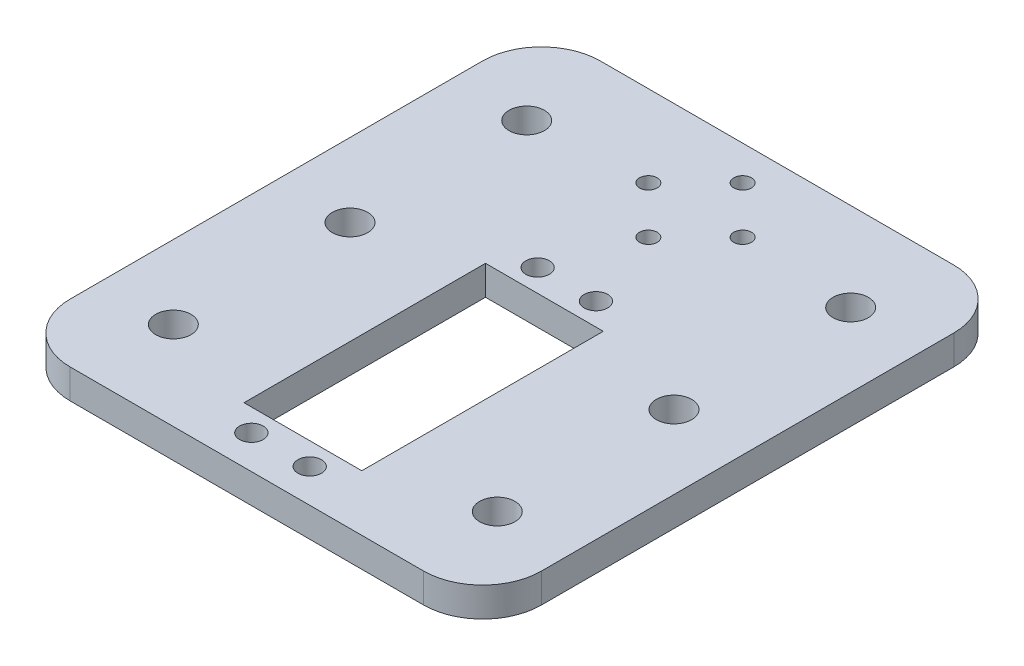
SolidWorks part; units mm, degrees
ref_plane "前视基准面" through (0, 0, 0) normal (0, 0, 1) x (1, 0, 0)
ref_plane "上视基准面" through (0, 0, 0) normal (0, 1, 0) x (1, 0, 0)
ref_plane "右视基准面" through (0, 0, 0) normal (1, 0, 0) x (0, 0, -1)
other "Configuration Table"
sketch "草图1" plane through (0, 0, 0) normal (0, 1, 0) x (1, 0, 0)
  line L0 (10, 50.306) -> (10, -41.9644) construction
  line L1 (-40, -30) -> (40, -30)
  line L2 (-40, -30) -> (-40, 60)
  line L4 (40, -30) -> (40, 60)
  line L5 (0, 30) -> (0, -30) construction
  line L6 (-40, 0) -> (40, 0) construction
  line L7 (-10, 50.306) -> (-10, -41.9644) construction
  line L8 (-40, 60) -> (40, 60)
  line L13 (-10, -20.5) -> (10, -20.5)
  line L14 (-10, -20.5) -> (-10, 20.5)
  line L15 (-10, 20.5) -> (10, 20.5)
  line L16 (10, -20.5) -> (10, 20.5)
  line L17 (0, 20.5) -> (0, -20.5) construction
  line L18 (-10, 0) -> (10, 0) construction
  line L19 (-27.5, 15) -> (-27.5, 45) construction
  circle A0 centre (27.5, 15) radius 3
  circle A1 centre (27.5, -15) radius 3
  circle A2 centre (-27.5, -15) radius 3
  circle A3 centre (-27.5, 15) radius 3
  circle A6 centre (4.95, 24.3) radius 2
  circle A7 centre (-4.95, 24.3) radius 2
  circle A8 centre (4.95, -24.3) radius 2
  circle A9 centre (-4.95, -24.3) radius 2
  circle A10 centre (-27.5, 45) radius 3
  circle A11 centre (27.5, 45) radius 3
  point P24 (0, 0)
  dimension "D4" = 6
  dimension "D7" = 80
  dimension "D9" = 12.5
  dimension "D3" = 4
  dimension "D1" = 20
  dimension "D2" = 30
  dimension "D5" = 48.6
  dimension "D6" = 30
  dimension "D8" = 9.9
  dimension "D10" = 41
  dimension "D11" = 60
  dimension "D13" = 30
  dimension "D12" = 2
extrude "凸台-拉伸1" add sketch "草图1" along normal blind 5
fillet "圆角1" radius 10 4 edges at (-40, 2.5, -60) (40, 2.5, -60) (40, 2.5, 30) (-40, 2.5, 30)
sketch "草图2" plane through (0, 0, 0) normal (0, 1, 0) x (1, 0, 0)
  line L5 (-34.4048, 46.15) -> (39.1378, 46.15) construction
  line L6 (0, 87.7765) -> (0, -51.5351) construction
  circle A1 centre (0, 46.15) radius 8 construction
  circle A2 centre (0, 54.15) radius 1.5
  circle A3 centre (8, 46.15) radius 1.5
  circle A4 centre (0, 38.15) radius 1.5
  circle A5 centre (-8, 46.15) radius 1.5
  point P15 (0, 0)
  point P24 (0, 46.15)
  dimension "D4" = 16
  dimension "D5" = 3
  dimension "D1" = 46.15
  dimension "D6" = 4
extrude "切除-拉伸1" cut sketch "草图2" along normal through all
